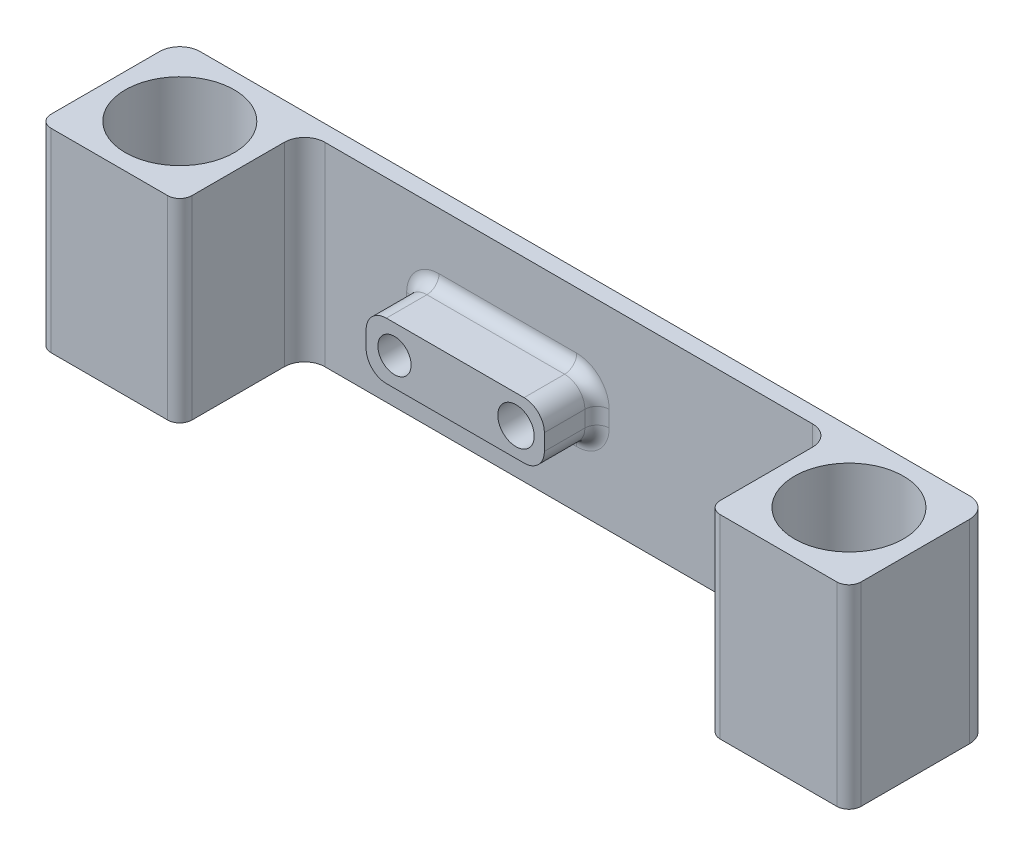
SolidWorks part; units mm, degrees
ref_plane "Front Plane" through (0, 0, 0) normal (0, 0, 1) x (1, 0, 0)
ref_plane "Top Plane" through (0, 0, 0) normal (0, 1, 0) x (1, 0, 0)
ref_plane "Right Plane" through (0, 0, 0) normal (1, 0, 0) x (0, 0, -1)
sketch "Sketch1" plane through (0, 0, 0) normal (0, 1, 0) x (1, 0, 0)
  line L1 (-17.4, 17.4) -> (17.4, 17.4)
  line L2 (-17.4, 13.4) -> (-17.4, -17.4)
  line L3 (-17.4, -17.4) -> (17.4, -17.4)
  line L4 (17.4, 17.4) -> (17.4, -17.4)
  line L5 (0, -17.4) -> (0, 17.4) construction
  line L6 (-17.4, 0) -> (17.4, 0) construction
  line L7 (-17.4, 17.4) -> (-82.6, 17.4)
  line L9 (-17.4, 13.4) -> (-82.6, 13.4)
  line L10 (-82.6, 17.4) -> (-82.6, 13.4)
  circle A0 centre (0, 0) radius 13.45
  dimension "D1" = 26.9
  dimension "D2" = 34.8
  dimension "D3" = 34.8
  dimension "D4" = 65.2
  dimension "D5" = 4
extrude "Boss-Extrude2" add sketch "Sketch1" along normal blind 48
mirror "Mirror2" about plane through (-82.6, 48, -17.4) normal (1, 0, 0) of "Boss-Extrude2"
sketch "Sketch7" plane through (0, 0, -13.4) normal (0, 0, 1) x (1, 0, 0)
  line L0 (-147.8, 24) -> (-17.4, 24) construction
  line L1 (-147.8, 48) -> (-147.8, 0) construction
  line L2 (-17.4, 48) -> (-17.4, 0) construction
  line L3 (-82.6, 48) -> (-82.6, 0) construction
  line L4 (-147.8, 48) -> (-17.4, 48) construction
  line L5 (-147.8, 0) -> (-17.4, 0) construction
  line L6 (-112.6, 24) -> (-82.6, 24) construction
  line L8 (-119.6, 17) -> (-75.6, 17)
  line L9 (-119.6, 17) -> (-119.6, 31)
  line L10 (-119.6, 31) -> (-75.6, 31)
  line L11 (-75.6, 17) -> (-75.6, 31)
  line L12 (-97.6, 31) -> (-97.6, 17) construction
  line L13 (-119.6, 24) -> (-75.6, 24) construction
  circle A0 centre (-82.6, 24) radius 4.5
  circle A2 centre (-112.6, 24) radius 4.1
  point P15 (-97.6, 24)
  dimension "D1" = 9
  dimension "D3" = 8.2
  dimension "D5" = 30
  dimension "D2" = 14
  dimension "D4" = 44
extrude "Boss-Extrude3" add sketch "Sketch7" along normal blind 13
fillet "Fillet1" radius 3 4 edges at (17.4, 24, 17.4) (-17.4, 24, 17.4) (-182.6, 24, 17.4) (-147.8, 24, 17.4)
fillet "Fillet2" radius 5 4 edges at (-17.4, 24, -13.4) (17.4, 24, -17.4) (-182.6, 24, -17.4) (-147.8, 24, -13.4)
fillet "Fillet3" radius 5 4 edges at (-75.6, 31, -6.9) (-75.6, 17, -6.9) (-119.6, 31, -6.9) (-119.6, 17, -6.9)
fillet "Fillet4" radius 3 8 edges at (-118.1355, 18.4645, -13.4) (-119.6, 24, -13.4) (-118.1355, 29.5355, -13.4) (-97.6, 31, -13.4) (-77.0645, 29.5355, -13.4) (-75.6, 24, -13.4) (-77.0645, 18.4645, -13.4) (-97.6, 17, -13.4)
sketch "Sketch8" plane through (0, 0, -13.4) normal (0, 0, 1) x (1, 0, 0)
  circle A0 centre (-112.6, 24) radius 4.1 construction
  circle A1 centre (-82.6, 24) radius 4.5 construction
  circle A2 centre (-112.6, 24) radius 4.1
  circle A3 centre (-82.6, 24) radius 4.5
extrude "Cut-Extrude1" cut sketch "Sketch8" against normal through all
